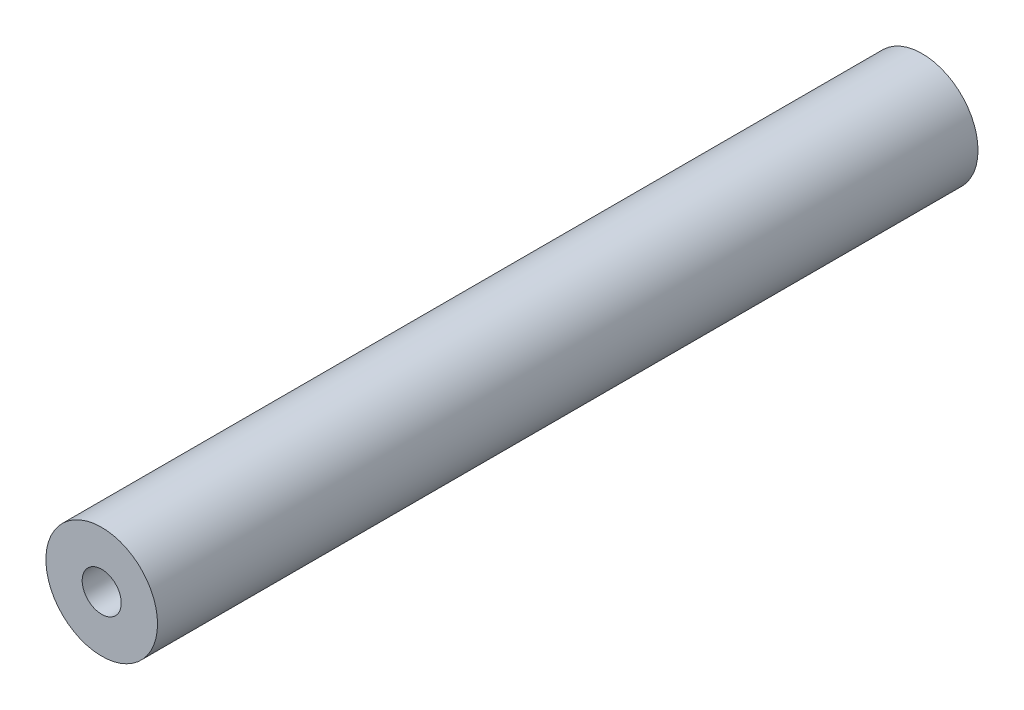
SolidWorks part; units mm, degrees
ref_plane "前视基准面" through (0, 0, 0) normal (0, 0, 1) x (1, 0, 0)
ref_plane "上视基准面" through (0, 0, 0) normal (0, 1, 0) x (1, 0, 0)
ref_plane "右视基准面" through (0, 0, 0) normal (1, 0, 0) x (0, 0, -1)
sketch "草图1" plane through (0, 0, 0) normal (0, 0, 1) x (1, 0, 0)
  circle A0 centre (0, 0) radius 5
  circle A1 centre (0, 0) radius 1.75
  dimension "D1" = 3.5
  dimension "D2" = 10
extrude "凸台-拉伸1" add sketch "草图1" along normal blind 73.5
